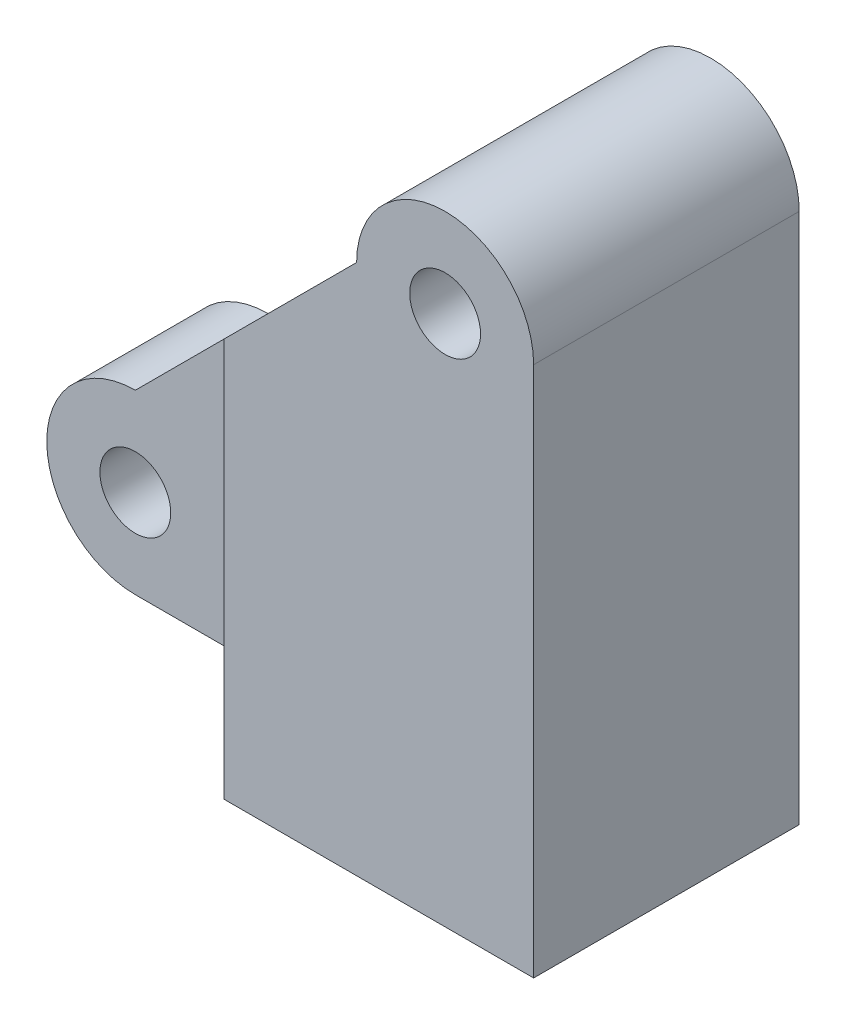
SolidWorks part; units mm, degrees
material "Dökme Alaşımlı Çelik"
ref_plane "Ön Düzlem" through (0, 0, 0) normal (0, 0, 1) x (1, 0, 0)
ref_plane "Üst Düzlem" through (0, 0, 0) normal (0, 1, 0) x (1, 0, 0)
ref_plane "Sağ Düzlem" through (0, 0, 0) normal (1, 0, 0) x (0, 0, -1)
sketch "Sketch1" plane through (0, 0, 0) normal (0, 0, 1) x (1, 0, 0)
  line L0 (0, 0) -> (50, 0) construction
  line L1 (50, 0) -> (50, 50) construction
  line L2 (50, 50) -> (0, 0) construction
  line L3 (0, -10) -> (60, -10)
  line L4 (60, -10) -> (60, 50)
  line L5 (40, 50) -> (0, 10)
  arc A0 (0, 10) -> (0, -10) centre (0, 0) ccw
  arc A1 (60, 50) -> (40, 50) centre (50, 50) ccw
  circle A2 centre (50, 50) radius 4
  circle A3 centre (0, 0) radius 4
  dimension "D3" = 10
  dimension "D4" = 10
  dimension "D1" = 50
  dimension "D2" = 50
extrude "Boss-Extrude1" add sketch "Sketch1" along normal blind 30
sketch "Sketch3" plane through (0, 0, 30) normal (0, 0, 1) x (1, 0, 0)
  line L0 (60, -10) -> (25, -10) construction
  line L1 (0, -10) -> (60, -10) construction
  line L2 (60, -10) -> (25, -10)
  line L3 (25, -10) -> (25, 35)
  line L4 (40, 50) -> (0, 10) construction
  line L5 (60, -10) -> (60, 50) construction
  line L6 (0, -10) -> (60, -10)
  line L7 (40, 50) -> (0, 10)
  line L8 (60, -10) -> (60, 50)
  arc A0 (60, 50) -> (40, 50) centre (50, 50) ccw construction
  arc A1 (60, 50) -> (40, 50) centre (50, 50) ccw
  arc A2 (0, 10) -> (0, -10) centre (0, 0) ccw construction
  arc A3 (0, 10) -> (0, -10) centre (0, 0) ccw
  dimension "D1" = 35
extrude "Cut-Extrude3" cut sketch "Sketch3" against normal blind 15 contours L2 L3 L5 L1 L7
